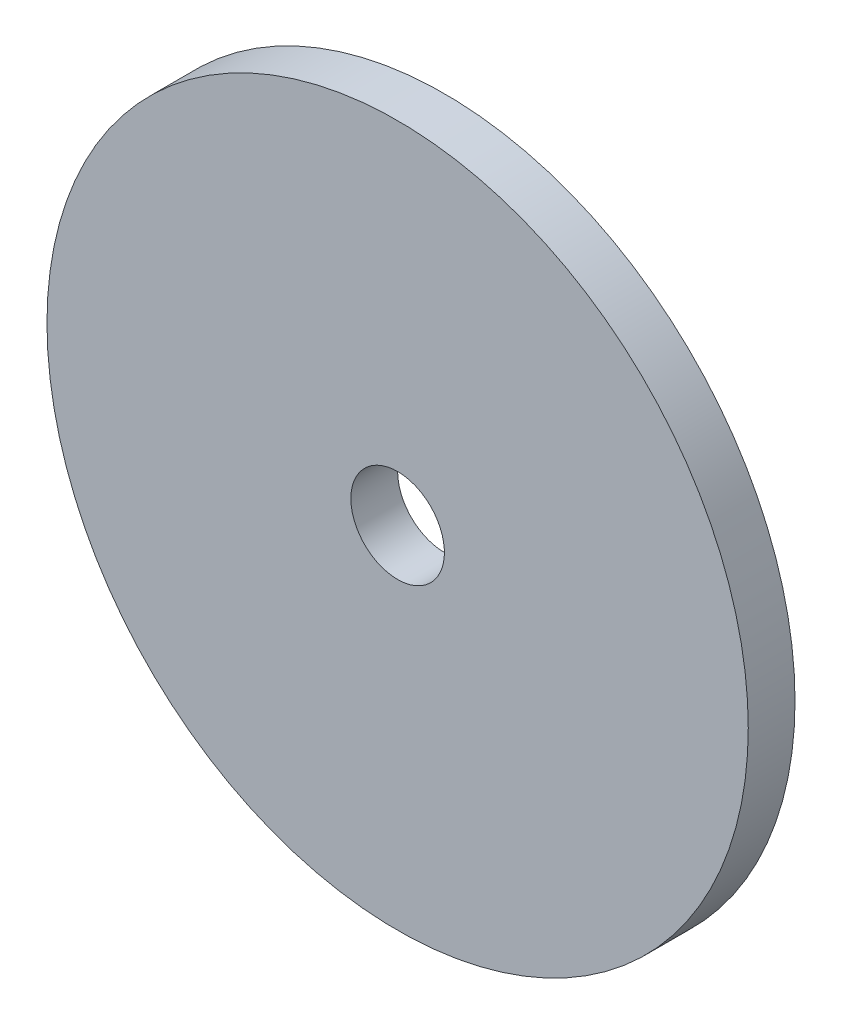
SolidWorks part; units mm, degrees
ref_plane "前视基准面" through (0, 0, 0) normal (0, 0, 1) x (1, 0, 0)
ref_plane "上视基准面" through (0, 0, 0) normal (0, 1, 0) x (1, 0, 0)
ref_plane "右视基准面" through (0, 0, 0) normal (1, 0, 0) x (0, 0, -1)
other "Configuration Table"
sketch "草图1" plane through (0, 0, 0) normal (0, 0, 1) x (1, 0, 0)
  circle A0 centre (0, 0) radius 11.25
  point P3 (0, 0)
  dimension "D1" = 22.5
extrude "凸台-拉伸1" add sketch "草图1" along normal blind 1.5
sketch "草图3" plane through (0, 0, 0) normal (0, 1, 0) x (1, 0, 0)
  line L0 (-11.25, -1.5) -> (11.25, -1.5) construction
  line L1 (0, 0) -> (1.5, 0)
  line L2 (0, 0) -> (0, -1.5)
  line L3 (0, -1.5) -> (1.5, -1.5)
  line L4 (1.5, 0) -> (1.5, -1.5)
  dimension "D1" = 1.5
revolve "切除-旋转1" cut sketch "草图3" angle 360 about L2
